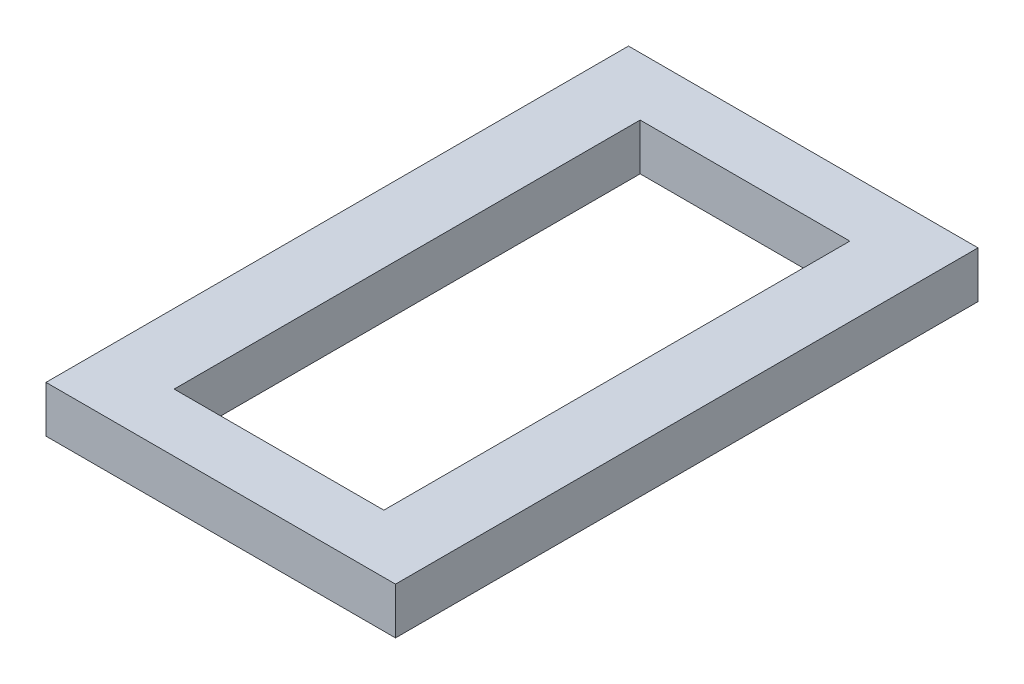
SolidWorks part; units mm, degrees
ref_plane "Front Plane" through (0, 0, 0) normal (0, 0, 1) x (1, 0, 0)
ref_plane "Top Plane" through (0, 0, 0) normal (0, 1, 0) x (1, 0, 0)
ref_plane "Right Plane" through (0, 0, 0) normal (1, 0, 0) x (0, 0, -1)
sketch "Sketch1" plane through (0, 0, 0) normal (0, 1, 0) x (1, 0, 0)
  line L1 (-22.5, 37.5) -> (22.5, 37.5)
  line L2 (-22.5, 37.5) -> (-22.5, -37.5)
  line L3 (-22.5, -37.5) -> (22.5, -37.5)
  line L4 (22.5, 37.5) -> (22.5, -37.5)
  line L5 (-22.5, 37.5) -> (22.5, -37.5) construction
  line L6 (-22.5, -37.5) -> (22.5, 37.5) construction
  line L7 (-13.5, 30) -> (13.5, 30)
  line L8 (-13.5, 30) -> (-13.5, -30)
  line L9 (-13.5, -30) -> (13.5, -30)
  line L10 (13.5, 30) -> (13.5, -30)
  line L11 (-13.5, 30) -> (13.5, -30) construction
  line L12 (-13.5, -30) -> (13.5, 30) construction
  point P0 (0, 0)
  point P6 (0, 0)
  dimension "D1" = 75
  dimension "D2" = 45
  dimension "D3" = 27
  dimension "D4" = 60
extrude "Boss-Extrude1" add sketch "Sketch1" along normal blind 6
